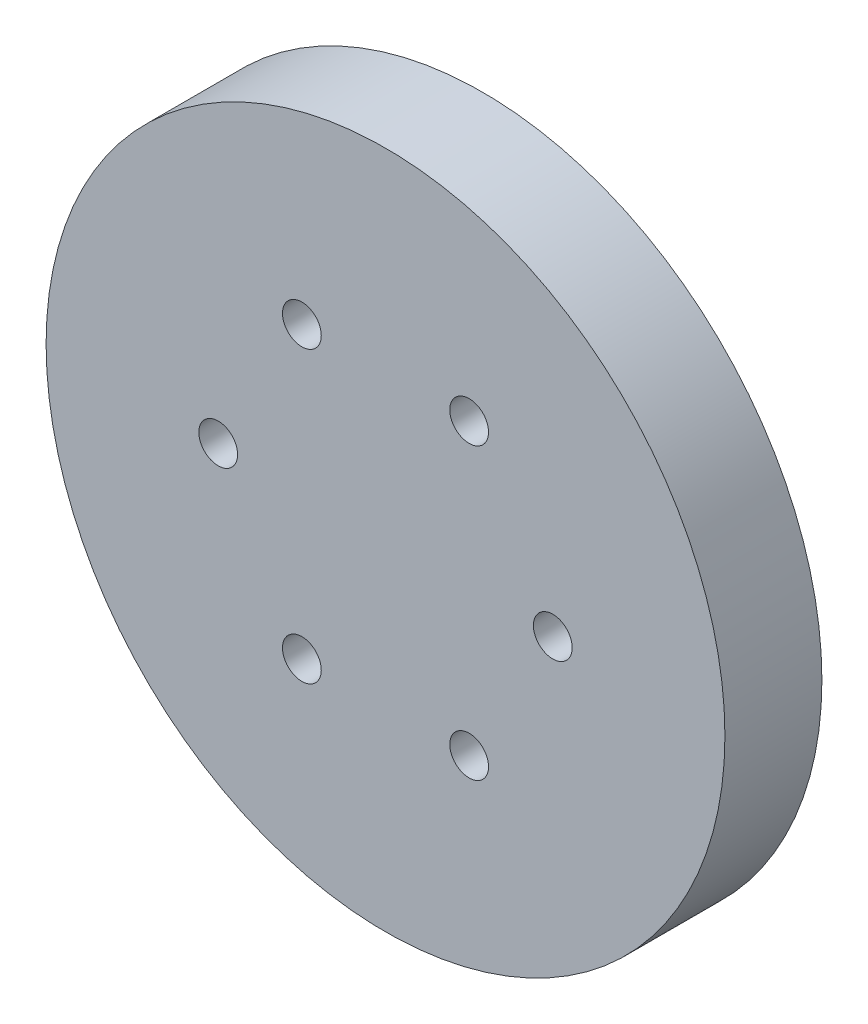
SolidWorks part; units mm, degrees
ref_plane "前视基准面" through (0, 0, 0) normal (0, 0, 1) x (1, 0, 0)
ref_plane "上视基准面" through (0, 0, 0) normal (0, 1, 0) x (1, 0, 0)
ref_plane "右视基准面" through (0, 0, 0) normal (1, 0, 0) x (0, 0, -1)
sketch "草图1" plane through (0, 0, 0) normal (0, 0, 1) x (1, 0, 0)
  circle A0 centre (0, 0) radius 35
  circle A1 centre (0, 0) radius 17.25
  circle A2 centre (-17.25, 0) radius 2
  circle A3 centre (-8.625, 14.9389) radius 2
  circle A4 centre (8.625, 14.9389) radius 2
  circle A5 centre (17.25, 0) radius 2
  circle A6 centre (8.625, -14.9389) radius 2
  circle A7 centre (-8.625, -14.9389) radius 2
  point P18 (0, 0)
  dimension "D1" = 70
  dimension "D2" = 34.5
  dimension "D3" = 6
extrude "凸台-拉伸1" add sketch "草图1" along normal blind 10 contours A0 A7 A1 A2 A3 A4 A5 A6 | A7 A1 A6 A5 A4 A3 A2
